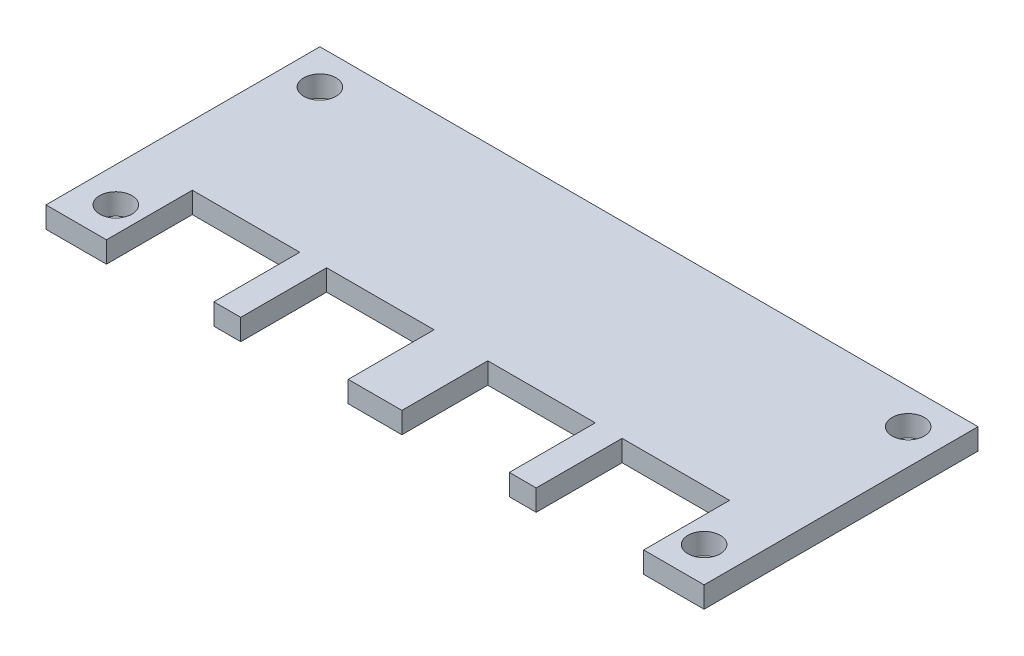
SolidWorks part; units mm, degrees
ref_plane "Front Plane" through (0, 0, 0) normal (0, 0, 1) x (1, 0, 0)
ref_plane "Top Plane" through (0, 0, 0) normal (0, 1, 0) x (1, 0, 0)
ref_plane "Right Plane" through (0, 0, 0) normal (1, 0, 0) x (0, 0, -1)
sketch "Sketch1" plane through (0, 0, 0) normal (0, 1, 0) x (1, 0, 0)
  line L1 (0, 0) -> (62.23, 0)
  line L2 (0, 0) -> (0, 25.9)
  line L3 (0, 25.9) -> (62.23, 25.9)
  line L4 (62.23, 0) -> (62.23, 25.9)
  dimension "D1" = 62.23
  dimension "D2" = 25.9
extrude "Boss-Extrude1" add sketch "Sketch1" along normal blind 2
sketch "Sketch2" plane through (0, 2, 0) normal (0, 1, 0) x (1, 0, 0)
  line L0 (3.3, 25.9) -> (3.3, 22.6) construction
  line L1 (62.23, 25.9) -> (0, 25.9) construction
  line L2 (0, 25.9) -> (0, 0) construction
  line L3 (0, 12.95) -> (62.23, 12.95) construction
  line L4 (62.23, 0) -> (62.23, 25.9) construction
  line L5 (31.115, 12.95) -> (31.115, 25.9) construction
  line L6 (31.115, 0) -> (31.115, 4.06) construction
  line L7 (0, 0) -> (62.23, 0) construction
  line L8 (31.115, 4.06) -> (38.735, 4.06) construction
  line L9 (38.735, 4.06) -> (51.435, 4.06) construction
  line L10 (43.815, 8.12) -> (33.655, 8.12)
  line L11 (43.815, 8.12) -> (43.815, 0)
  line L12 (43.815, 0) -> (33.655, 0)
  line L13 (33.655, 8.12) -> (33.655, 0)
  line L14 (43.815, 8.12) -> (33.655, 0) construction
  line L15 (43.815, 0) -> (33.655, 8.12) construction
  line L16 (5.715, 8.12) -> (15.875, 8.12)
  line L17 (56.515, 0) -> (46.355, 0)
  line L18 (56.515, 0) -> (56.515, 8.12)
  line L19 (56.515, 8.12) -> (46.355, 8.12)
  line L20 (46.355, 0) -> (46.355, 8.12)
  line L21 (56.515, 0) -> (46.355, 8.12) construction
  line L22 (56.515, 8.12) -> (46.355, 0) construction
  line L23 (15.875, 0) -> (15.875, 8.12)
  line L24 (5.715, 0) -> (15.875, 0)
  line L25 (5.715, 0) -> (5.715, 8.12)
  line L26 (18.415, 0) -> (28.575, 0)
  line L27 (28.575, 8.12) -> (28.575, 0)
  line L28 (18.415, 8.12) -> (28.575, 8.12)
  line L29 (18.415, 8.12) -> (18.415, 0)
  circle A0 centre (3.3, 22.6) radius 1.524
  circle A1 centre (3.3, 3.3) radius 1.524
  circle A2 centre (58.93, 3.3) radius 1.524
  circle A3 centre (58.93, 22.6) radius 1.524
  point P41 (23.495, 0)
  point P42 (38.735, 0)
  dimension "D3" = 3.048
  dimension "D1" = 3.3
  dimension "D2" = 3.3
  dimension "D4" = 15.24
  dimension "D5" = 12.7
  dimension "D6" = 4.06
  dimension "D7" = 10.16
  dimension "D8" = 8.12
extrude "Cut-Extrude1" cut sketch "Sketch2" against normal blind 10
